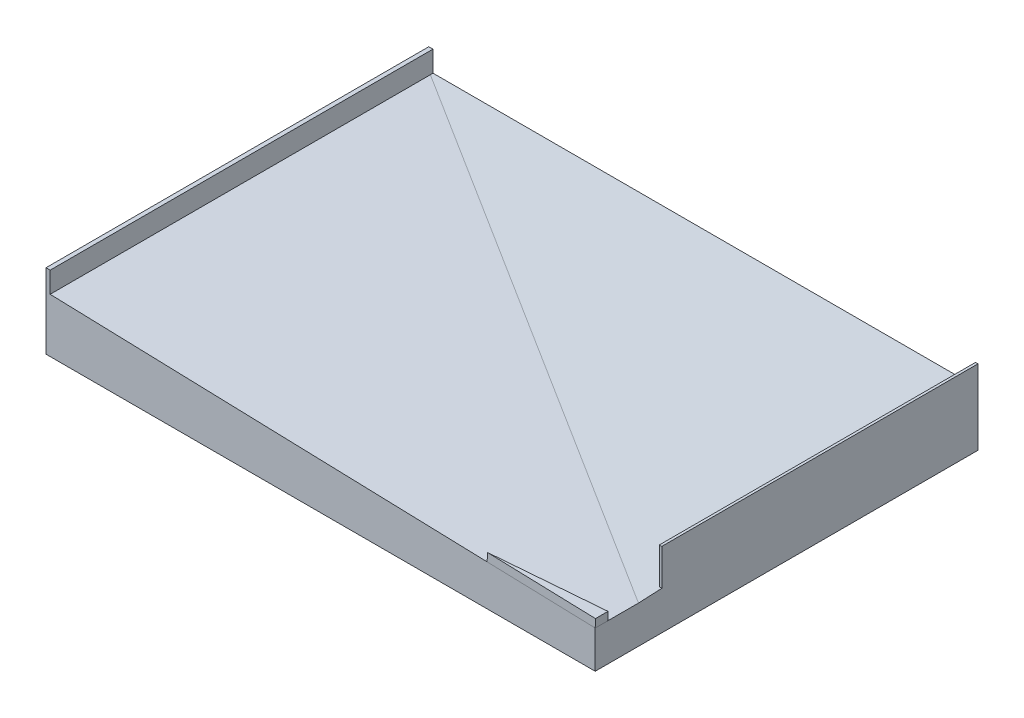
SolidWorks part; units mm, degrees
ref_plane "Front Plane" through (0, 0, 0) normal (0, 0, 1) x (1, 0, 0)
ref_plane "Top Plane" through (0, 0, 0) normal (0, 1, 0) x (1, 0, 0)
ref_plane "Right Plane" through (0, 0, 0) normal (1, 0, 0) x (0, 0, -1)
sketch "Sketch3" plane through (0, 0, 0) normal (0, 0, 1) x (1, 0, 0)
  line L0 (-419.1, 0) -> (419.1, 0)
  line L1 (-419.1, 0) -> (-419.1, 82.55)
  line L2 (-419.1, 82.55) -> (419.1, 57.15)
  line L3 (419.1, 57.15) -> (419.1, 0)
  line L4 (419.1, 57.15) -> (-419.1, 57.15) construction
  point P3 (0, 0)
  dimension "D1" = 838.2
  dimension "D2" = 57.15
  dimension "D3" = 82.55
  dimension "D4" = 1.736
extrude "Boss-Extrude2" add sketch "Sketch3" against normal blind 584.2
sketch "Sketch4" plane through (419.1, 0, 0) normal (1, 0, 0) x (0, 0, -1)
  line L0 (0, 57.15) -> (66.04, 57.15) construction
  line L1 (584.2, 57.15) -> (0, 57.15) construction
  line L2 (0, 0) -> (0, 57.15) construction
  line L3 (66.04, 57.15) -> (66.04, 0)
  line L4 (584.2, 0) -> (0, 0) construction
  line L5 (66.04, 0) -> (584.2, 0)
  line L6 (584.2, 0) -> (584.2, 82.55)
  line L7 (584.2, 82.55) -> (66.04, 57.15)
  dimension "D1" = 66.04
extrude "Boss-Extrude3" add sketch "Sketch4" against normal up to surface (838.2 mm away) up to face at (-419.1, 41.275, -292.1)
sketch "Sketch5" plane through (0, 0, 0) normal (0, 1, 0) x (1, 0, 0)
  line L0 (-419.1, 0) -> (419.1, 584.2) construction
  line L1 (419.1, 0) -> (-419.1, 584.2) construction
  line L3 (-419.1, 584.2) -> (-412.75, 584.2)
  line L4 (-419.1, 584.2) -> (-419.1, 0)
  line L6 (419.1, 584.2) -> (419.1, 101.6)
  line L7 (-419.1, 584.2) -> (419.1, 0) construction
  line L8 (-419.1, 0) -> (419.1, 584.2) construction
  line L10 (-412.75, 579.7742) -> (-412.75, 6.35)
  line L12 (415.3331, 579.6383) -> (415.3331, 101.6)
  line L13 (-412.75, 579.7742) -> (410.1194, 6.2592) construction
  line L14 (-412.75, 6.35) -> (415.3331, 579.6383) construction
  line L19 (-412.75, 579.7742) -> (-412.75, 584.2)
  line L20 (415.3331, 579.6383) -> (415.3331, 584.2)
  line L21 (415.3331, 584.2) -> (419.1, 584.2)
  line L22 (-412.75, 6.35) -> (-412.75, 0)
  line L23 (419.1, 0) -> (-419.1, 0) construction
  line L24 (-419.1, 0) -> (-412.75, 0)
  line L25 (419.1, 0) -> (482.9777, 0) construction
  line L26 (482.9777, 0) -> (482.9777, 65.532) construction
  line L27 (482.9777, 65.532) -> (440.1886, 65.532) construction
  line L28 (440.1886, 65.532) -> (440.1886, 101.6) construction
  line L29 (415.3331, 101.6) -> (419.1, 101.6)
  point P8 (0, 292.1)
  point P9 (0, 292.1)
  dimension "D1" = 6.35
  dimension "D2" = 3.7669
  dimension "D3" = 36.068
  dimension "D4" = 101.6
extrude "Boss-Extrude4" add sketch "Sketch5" along normal blind 114.3
sketch "Sketch6" plane through (2.1147, 69.7859, 0) normal (0.0303, 0.9995, 0) x (0.9995, -0.0303, 0)
  line L0 (417.1767, 0) -> (417.1767, 19.1293)
  line L1 (417.1767, 66.04) -> (417.1767, 0) construction
  line L2 (417.1767, 19.1293) -> (252.2153, 0)
  line L3 (417.1767, 0) -> (-415.0552, 0) construction
  line L4 (250.8113, 0) -> (417.1767, 0)
  line M3 (-415.0552, 0) -> (417.1767, 0)
  line M4 (417.1767, 0) -> (417.1767, 66.04)
extrude "Boss-Extrude5" add sketch "Sketch6" along normal blind 12.7 separate body contours L2 M4 M3
